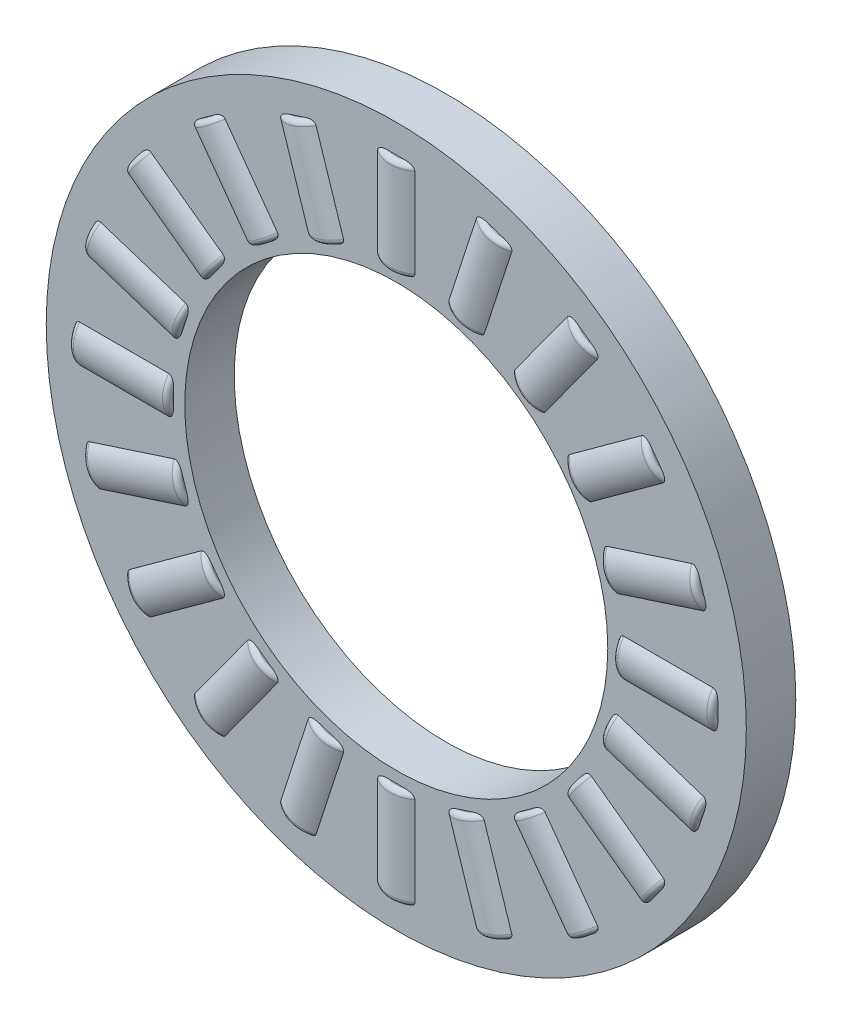
SolidWorks part; units mm, degrees
material "SPRING STEEL ASTM A 229"
ref_plane "Front Plane" through (0, 0, 0) normal (0, 0, 1) x (1, 0, 0)
ref_plane "Top Plane" through (0, 0, 0) normal (0, 1, 0) x (1, 0, 0)
ref_plane "Right Plane" through (0, 0, 0) normal (1, 0, 0) x (0, 0, -1)
sketch "Sketch1" plane through (0, 0, 0) normal (1, 0, 0) x (0, 0, -1)
  line L0 (0, 0) -> (44.392, 0) construction
  line L1 (0, 0) -> (0, 32.1562) construction
  line L3 (-1, 14.15) -> (1, 14.15)
  line L4 (-1, 14.15) -> (-1, 8.55)
  line L5 (-1, 8.55) -> (1, 8.55)
  line L6 (1, 14.15) -> (1, 8.55)
  dimension "D1" = 28.3
  dimension "D2" = 17.1
  dimension "D3" = 2
revolve "Revolve1" add sketch "Sketch1" angle 360 about L0
sketch "Sketch2" plane through (0, 0, 0) normal (1, 0, 0) x (0, 0, -1)
  line L0 (0, 0) -> (0, 21.8044) construction
  line L1 (0, 13) -> (1.05, 13)
  line L2 (1.25, 12.8) -> (1.25, 9.2)
  line L3 (1.05, 9) -> (0, 9)
  line L4 (0, 13) -> (0, 9)
  arc A0 (1.05, 13) -> (1.25, 12.8) centre (1.05, 12.8) cw
  arc A1 (1.25, 9.2) -> (1.05, 9) centre (1.05, 9.2) cw
  dimension "D4" = 0.2
  dimension "D1" = 2.5
  dimension "D2" = 4
  dimension "D3" = 13
revolve "Revolve2" add sketch "Sketch2" angle 360 about L0
pattern_circular "CirPattern1" count 20 over 360 about axis through (0, 0, 0) along (0, 0, 1) of "Revolve2"
